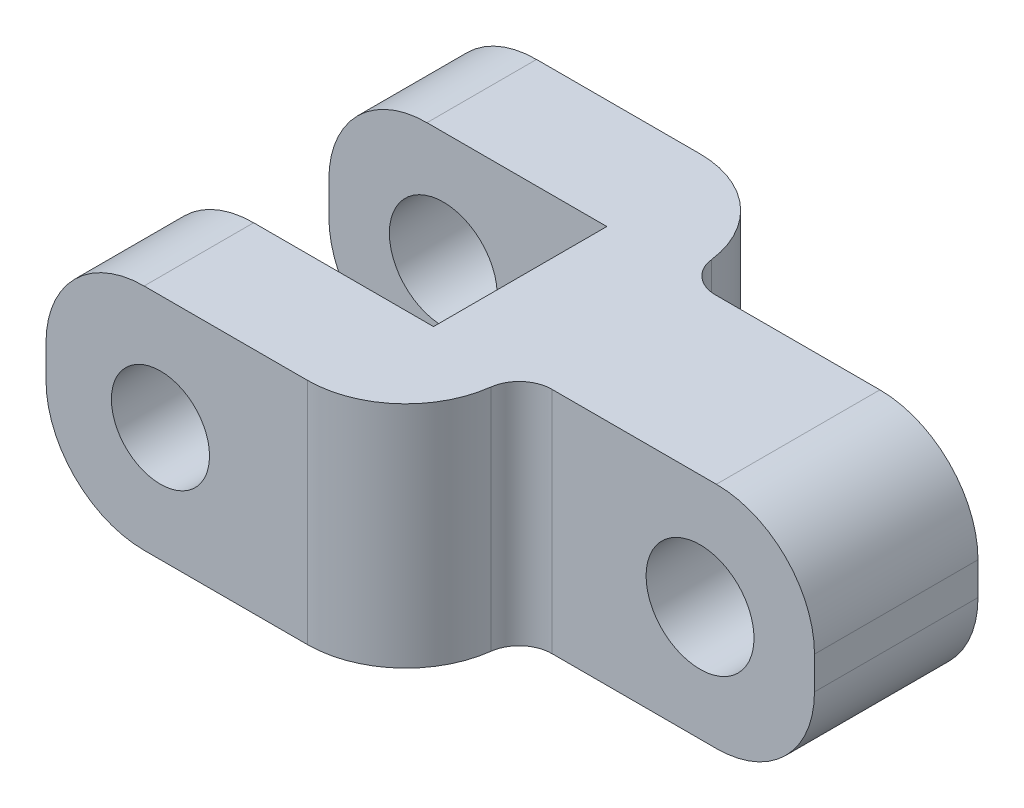
SolidWorks part; units mm, degrees
ref_plane "前视基准面" through (0, 0, 0) normal (0, 0, 1) x (1, 0, 0)
ref_plane "上视基准面" through (0, 0, 0) normal (0, 1, 0) x (1, 0, 0)
ref_plane "右视基准面" through (0, 0, 0) normal (1, 0, 0) x (0, 0, -1)
sketch "草图1" plane through (0, 0, 0) normal (0, 0, 1) x (1, 0, 0)
  line L0 (0, -55) -> (0, 55) construction
  line L1 (-10, 3.5) -> (10, 3.5)
  line L2 (-10, 3.5) -> (-10, -3.5)
  line L3 (-10, -3.5) -> (10, -3.5)
  line L4 (10, 3.5) -> (10, -3.5)
  line L5 (-10, 3.5) -> (10, -3.5) construction
  line L6 (-10, -3.5) -> (10, 3.5) construction
  circle A0 centre (-6.5, 0) radius 1.65
  circle A1 centre (6.5, 0) radius 1.65
  point P0 (0, 0)
  dimension "D3" = 3.3
  dimension "D1" = 7
  dimension "D2" = 20
  dimension "D4" = 6.5
extrude "凸台-拉伸1" add sketch "草图1" along normal blind 12
sketch "草图2" plane through (0, 3.5, 0) normal (0, 1, 0) x (1, 0, 0)
  line L0 (-10, -12) -> (-10, 0) construction
  line L1 (-10, -3.35) -> (-1.5, -3.35)
  line L2 (-10, -3.35) -> (-10, -8.65)
  line L3 (-10, -8.65) -> (-1.5, -8.65)
  line L4 (-1.5, -3.35) -> (-1.5, -8.65)
  line L6 (-10, 0) -> (-10, -3.35) construction
  line L7 (-10, -8.65) -> (-10, -12) construction
  dimension "D1" = 5.3
  dimension "D2" = 8.5
extrude "切除-拉伸1" cut sketch "草图2" against normal blind 12
sketch "草图3" plane through (0, 3.5, 0) normal (0, 1, 0) x (1, 0, 0)
  line L1 (10, 0) -> (1, 0)
  line L2 (10, 0) -> (10, -3.5)
  line L3 (10, -3.5) -> (1, -3.5)
  line L4 (1, 0) -> (1, -3.5)
  line L5 (10, -12) -> (1, -12)
  line L6 (10, -12) -> (10, -8.5)
  line L7 (10, -8.5) -> (1, -8.5)
  line L8 (1, -12) -> (1, -8.5)
  dimension "D1" = 5
  dimension "D2" = 9
extrude "切除-拉伸2" cut sketch "草图3" against normal blind 12
fillet "圆角1" radius 3 6 edges at (10, -3.5, 6) (10, 3.5, 6) (-10, -3.5, 10.325) (-10, -3.5, 1.675) (-10, 3.5, 10.325) (-10, 3.5, 1.675)
fillet "圆角2" radius 3 2 edges at (1, 0, 0) (1, 0, 12)
fillet "圆角3" radius 1 2 edges at (1, 0, 3.5) (1, 0, 8.5)
sketch "草图5" plane through (0, 0, 8.65) normal (0, 0, -1) x (-1, 0, 0)
  circle A0 centre (6.5, 0) radius 1.65 construction
  circle A1 centre (6.5, 0) radius 1.65
  circle A2 centre (6.5, 0) radius 1.5
  dimension "D1" = 3
extrude "凸台-拉伸2" add sketch "草图5" against normal up to surface (3.35 mm away) up to face at (-6.5404, 0, 12)
